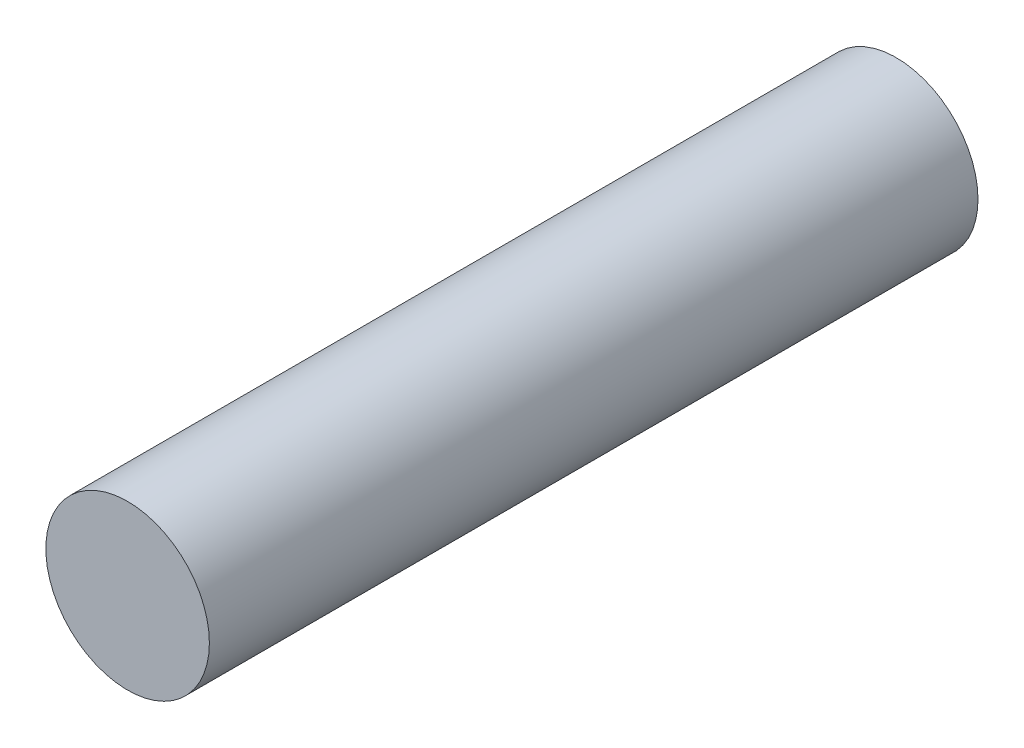
SolidWorks part; units mm, degrees
material "Chrome Stainless Steel"
ref_plane "Front Plane" through (0, 0, 0) normal (0, 0, 1) x (1, 0, 0)
ref_plane "Top Plane" through (0, 0, 0) normal (0, 1, 0) x (1, 0, 0)
ref_plane "Right Plane" through (0, 0, 0) normal (1, 0, 0) x (0, 0, -1)
sketch "Sketch1" plane through (0, 0, 0) normal (0, 0, 1) x (1, 0, 0)
  circle A0 centre (0, 0) radius 5
  dimension "D1" = 10
extrude "Boss-Extrude1" add sketch "Sketch1" along normal blind 47
